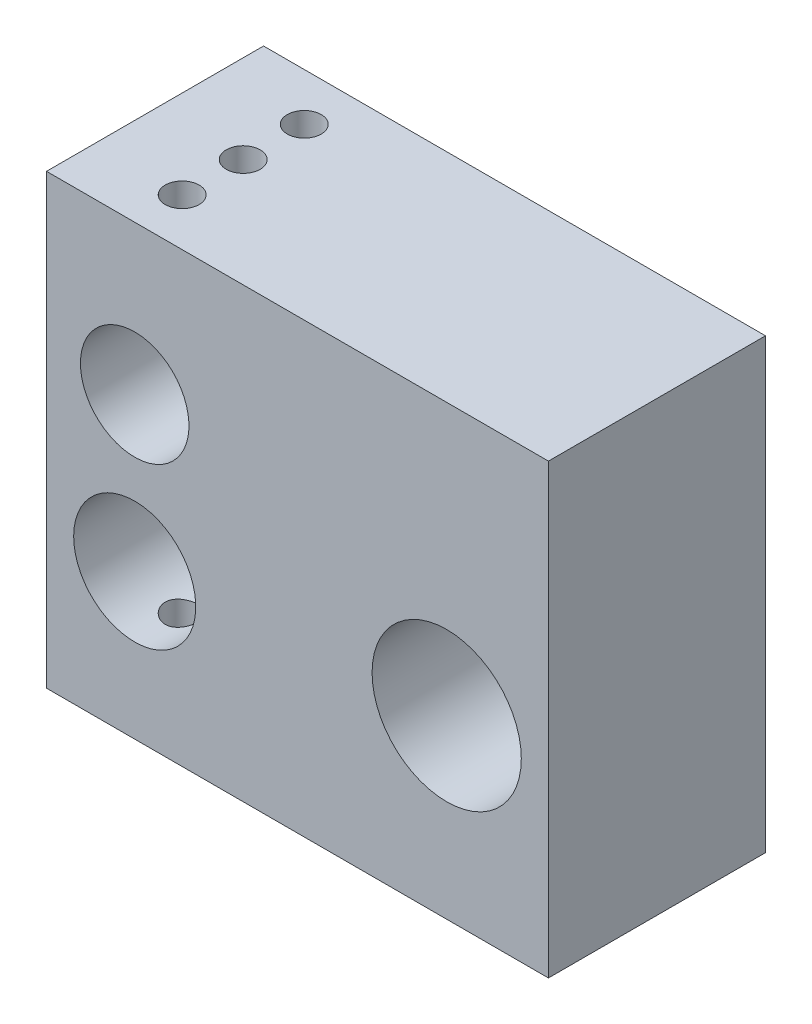
SolidWorks part; units mm, degrees
ref_plane "Plan de face" through (0, 0, 0) normal (0, 0, 1) x (1, 0, 0)
ref_plane "Plan de dessus" through (0, 0, 0) normal (0, 1, 0) x (1, 0, 0)
ref_plane "Plan de droite" through (0, 0, 0) normal (1, 0, 0) x (0, 0, -1)
sketch "Esquisse1" plane through (0, 0, 0) normal (0, 1, 0) x (1, 0, 0)
  line L1 (18.5, -8) -> (-18.5, -8)
  line L2 (18.5, -8) -> (18.5, 8)
  line L3 (18.5, 8) -> (-18.5, 8)
  line L4 (-18.5, -8) -> (-18.5, 8)
  line L5 (18.5, -8) -> (-18.5, 8) construction
  line L6 (18.5, 8) -> (-18.5, -8) construction
  point P0 (0, 0)
  dimension "D1" = 16
  dimension "D2" = 37
extrude "Boss.-Extru.1" add sketch "Esquisse1" along normal mid plane 33
sketch "Esquisse3" plane through (0, 0, 8) normal (0, 0, 1) x (1, 0, 0)
  line L0 (-18.5, -16.5) -> (18.5, -16.5) construction
  line L1 (18.5, 16.5) -> (18.5, -16.5) construction
  circle A0 centre (11, -3.5) radius 5.5
  dimension "D1" = 11
  dimension "D2" = 13
  dimension "D3" = 7.5
extrude "Enlèv. mat.-Extru.2" cut sketch "Esquisse3" against normal through all
sketch "Esquisse14" plane through (0, 0, -8) normal (0, 0, -1) x (-1, 0, 0)
  line L0 (-18.5, -16.5) -> (18.5, -16.5) construction
  line L1 (18.5, 16.5) -> (18.5, -16.5) construction
  circle A0 centre (12, -5.8) radius 4.5
  dimension "D1" = 9
  dimension "D2" = 10.7
  dimension "D3" = 6.5
extrude "Enlèv. mat.-Extru.3" cut sketch "Esquisse14" against normal through all
sketch "Esquisse15" plane through (0, 0, -8) normal (0, 0, -1) x (-1, 0, 0)
  line L0 (-18.5, -16.5) -> (18.5, -16.5) construction
  line L4 (18.5, 16.5) -> (18.5, -16.5) construction
  circle A0 centre (12, 5.5) radius 4
  dimension "D1" = 8
  dimension "D2" = 22
  dimension "D3" = 6.5
extrude "Enlèv. mat.-Extru.4" cut sketch "Esquisse15" against normal through all
hole_wizard "Trou taraudé M34" positions "Esquisse11" profile "Esquisse10" tap size "M3" standard "Iso"
sketch "Esquisse11" plane through (0, 16.5, 0) normal (0, 1, 0) x (1, 0, 0)
  line L0 (-12, -4.5) -> (-12, 4.5)
  line L14 (0, 0) -> (-12, 0) construction
  line L16 (-8, 8) -> (-16, 8) construction
  line L17 (-8, 8) -> (-16, 8)
  line L18 (-16, -8) -> (-8, -8) construction
  line L19 (-16, -8) -> (-8, -8)
  line L20 (-12, 8) -> (-12, 4.5) construction
  point P1 (-12, -4.5)
  point P2 (-12, 4.5)
  dimension "D1" = 3.5
cosmetic thread "Filetage de perçage11" parameters "D2"=3
cosmetic thread "Filetage de perçage12" parameters "D2"=3
sketch "Esquisse10" plane through (-12, 16.5, 4.5) normal (1, 0, 0) x (0, 0, 1)
  line L0 (0, 0) -> (0, 7)
  line L1 (0, 7) -> (1.25, 7)
  line L2 (1.25, 7) -> (1.25, 0)
  line L5 (1.25, 0) -> (0, 0)
  line L11 (0, -6.35) -> (0, 107.95) construction
  dimension "Diamètre du trou pour taraudage jusqu'au prochain" = 2.5
  dimension "Profondeur du trou pour taraudage jusqu'au prochain" = 7
hole_wizard "Trou taraudé M35" positions "Esquisse13" profile "Esquisse12" tap size "M3" standard "Iso"
sketch "Esquisse13" plane through (0, -16.5, 0) normal (0, -1, 0) x (-1, 0, 0)
  point P0 (12, -4.5)
  point P3 (12, 4.5)
cosmetic thread "Filetage de perçage9" parameters "D2"=3
cosmetic thread "Filetage de perçage10" parameters "D2"=3
sketch "Esquisse12" plane through (-12, -16.5, 4.5) normal (1, 0, 0) x (0, 0, -1)
  line L0 (0, 0) -> (0, 6.2)
  line L1 (0, 6.2) -> (1.25, 6.2)
  line L2 (1.25, 6.2) -> (1.25, 0)
  line L5 (1.25, 0) -> (0, 0)
  line L11 (0, -6.35) -> (0, 107.95) construction
  dimension "Diamètre du trou pour taraudage jusqu'au prochain" = 2.5
  dimension "Profondeur du trou pour taraudage jusqu'au prochain" = 6.2
hole_wizard "Trou taraudé M36" positions "Esquisse17" profile "Esquisse16" tap size "M3" standard "Iso"
sketch "Esquisse17" plane through (-1.446, 16.5, -0.3035) normal (0, -1, 0) x (-1, 0, 0)
  line L0 (6.554, -0.3035) -> (14.554, -0.3035)
  line L1 (6.554, 7.6965) -> (6.554, -8.3035) construction
  line L2 (14.554, -8.3035) -> (14.554, 7.6965) construction
  line L3 (14.554, -8.3035) -> (14.554, 7.6965)
  line L4 (6.554, 7.6965) -> (6.554, -8.3035)
  point P9 (10.554, -0.3035)
sketch "Esquisse16" plane through (-12, 16.5, 0) normal (1, 0, 0) x (0, 0, 1)
  line L0 (0, 0) -> (0, 7)
  line L1 (0, 7) -> (1.25, 7)
  line L2 (1.25, 7) -> (1.25, 0)
  line L5 (1.25, 0) -> (0, 0)
  line L11 (0, -6.35) -> (0, 107.95) construction
  dimension "Diamètre du trou pour taraudage jusqu'au prochain" = 2.5
  dimension "Profondeur du trou pour taraudage jusqu'au prochain" = 7
cosmetic thread "Filetage de perçage13" parameters "D2"=3
